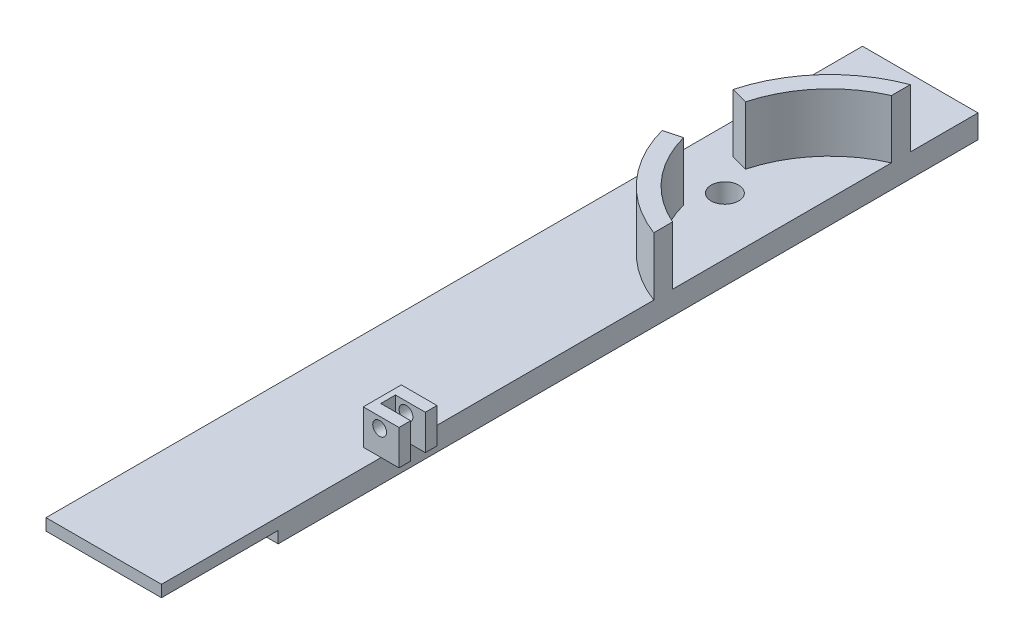
SolidWorks part; units mm, degrees
ref_plane "Front Plane" through (0, 0, 0) normal (0, 0, 1) x (1, 0, 0)
ref_plane "Top Plane" through (0, 0, 0) normal (0, 1, 0) x (1, 0, 0)
ref_plane "Right Plane" through (0, 0, 0) normal (1, 0, 0) x (0, 0, -1)
sketch "Sketch2" plane through (0, 0, 0) normal (0, 1, 0) x (1, 0, 0)
  line L1 (-10.6332, 33.9112) -> (14.5128, 33.9112)
  line L2 (-10.6332, 33.9112) -> (-10.6332, -143.8888)
  line L3 (-10.6332, -143.8888) -> (14.5128, -143.8888)
  line L4 (14.5128, 33.9112) -> (14.5128, -143.8888)
  dimension "D1" = 25.146
  dimension "D2" = 177.8
extrude "Boss-Extrude1" add sketch "Sketch2" along normal blind 5.08
sketch "Sketch4" plane through (0, 0, 0) normal (0, -1, 0) x (1, 0, 0)
  line L0 (14.5128, 143.8888) -> (14.5128, -33.9112) construction
  line L1 (-10.6332, 143.8888) -> (14.5128, 143.8888)
  line L2 (-10.6332, 143.8888) -> (-10.6332, 118.4888)
  line L3 (-10.6332, 118.4888) -> (14.5128, 118.4888)
  line L4 (14.5128, 143.8888) -> (14.5128, 118.4888)
  dimension "D1" = 25.4
extrude "Cut-Extrude2" cut sketch "Sketch4" against normal blind 2.54
sketch "Sketch5" plane through (0, 5.08, 0) normal (0, 1, 0) x (1, 0, 0)
  line L0 (14.5128, -143.8888) -> (14.5128, 33.9112) construction
  line L1 (14.5128, 33.9112) -> (-10.6332, 33.9112) construction
  line L2 (14.5128, 19.171) -> (14.5128, 15.0625)
  line L3 (14.5128, -32.5841) -> (14.5128, -36.6926)
  line L4 (24.9268, -8.7608) -> (-3.8674, -1.0454) construction
  line L5 (24.9268, -8.7608) -> (-3.8674, -16.4762) construction
  line L6 (24.9268, -8.7608) -> (-10.6332, -8.7608) construction
  line L7 (-10.6332, 33.9112) -> (-10.6332, -143.8888) construction
  line L8 (-3.8674, -1.0454) -> (-0.1872, -2.0315)
  line L9 (-3.8674, -16.4762) -> (-0.1872, -15.4901)
  arc A0 (14.5128, 15.0625) -> (-0.1872, -2.0315) centre (24.9268, -8.7608) ccw
  arc A1 (14.5128, 19.171) -> (-3.8674, -1.0454) centre (24.9268, -8.7608) ccw
  arc A2 (-0.1872, -15.4901) -> (14.5128, -32.5841) centre (24.9268, -8.7608) ccw
  arc A3 (-3.8674, -16.4762) -> (14.5128, -36.6926) centre (24.9268, -8.7608) ccw
  dimension "D1" = 10.414
  dimension "D2" = 42.672
  dimension "D3" = 3.81
  dimension "D4" = 52
  dimension "D5" = 15
  dimension "D6" = 15
extrude "Boss-Extrude2" add sketch "Sketch5" along normal blind 12.7
sketch "Sketch6" plane through (0, 0, 0) normal (0, -1, 0) x (1, 0, 0)
  line L0 (14.5128, 118.4888) -> (14.5128, -33.9112) construction
  line L1 (14.5128, -33.9112) -> (-10.6332, -33.9112) construction
  circle A0 centre (2.0668, 8.7608) radius 3
  dimension "D1" = 6
  dimension "D2" = 12.446
  dimension "D3" = 42.672
extrude "Cut-Extrude3" cut sketch "Sketch6" against normal through all
sketch "Sketch7" plane through (0, 5.08, 0) normal (0, 1, 0) x (1, 0, 0)
  line L0 (14.5128, -32.5841) -> (14.5128, 15.0625) construction
  line L1 (5.5918, -1.6036) -> (8.3544, -2.5309)
  line L2 (14.5128, 9.0329) -> (14.5128, 5.5572)
  line L3 (4.006, -16.4452) -> (6.7003, -15.8594)
  line L4 (14.5128, -28.4656) -> (14.5128, -25.3181)
  arc A0 (14.5128, -28.4656) -> (4.006, -16.4452) centre (24.9268, -8.7608) cw
  arc A1 (14.5128, 9.0329) -> (5.5918, -1.6036) centre (24.9268, -8.7608) ccw
  arc A2 (14.5128, 5.5572) -> (8.3544, -2.5309) centre (24.9268, -8.7608) ccw
  arc A3 (14.5128, -25.3181) -> (6.7003, -15.8594) centre (24.9268, -8.7608) cw
sketch "Sketch8" plane through (0, 5.08, 0) normal (0, 1, 0) x (1, 0, 0)
  line L0 (14.5128, -143.8888) -> (14.5128, -36.6926) construction
  line L1 (18.4097, -87.7914) -> (11.9097, -87.7914)
  line L2 (18.4097, -87.7914) -> (18.4097, -90.3314)
  line L3 (18.4097, -90.3314) -> (11.9097, -90.3314)
  line L4 (11.9097, -87.7914) -> (11.9097, -90.3314)
  line L6 (18.4097, -93.5314) -> (11.9097, -93.5314)
  line L7 (18.4097, -93.5314) -> (18.4097, -96.0714)
  line L8 (18.4097, -96.0714) -> (11.9097, -96.0714)
  line L9 (11.9097, -93.5314) -> (11.9097, -96.0714)
  line L10 (11.9097, -96.0714) -> (10.6397, -96.0714)
  line L11 (11.9097, -96.0714) -> (11.9097, -87.7914)
  line L12 (11.9097, -87.7914) -> (10.6397, -87.7914)
  line L13 (10.6397, -96.0714) -> (10.6397, -87.7914)
  line M24 (14.5128, -143.8888) -> (14.5128, -36.6926)
  dimension "D1" = 3.2
  dimension "D2" = 2.54
  dimension "D3" = 2.54
  dimension "D4" = 1.27
  dimension "D5" = 6.5
  dimension "D6" = 0
  dimension "D7" = 2.6032
extrude "Boss-Extrude3" add sketch "Sketch8" along normal blind 7.62 contours L13 L10 L9 L11 L4 L12 | L1 L4 L3 M24 | L6 L9 L8 M24
sketch "Sketch9" plane through (0, 0, 96.0714) normal (0, 0, 1) x (1, 0, 0)
  line L0 (10.6397, 5.4857) -> (14.1957, 5.4857) construction
  line L1 (10.6397, 12.7) -> (10.6397, 5.08) construction
  line L2 (14.1957, 5.08) -> (14.1957, 10.414) construction
  line L3 (14.5128, 5.08) -> (10.6397, 5.08) construction
  circle A0 centre (14.1957, 10.414) radius 1.5
  dimension "D1" = 3.556
  dimension "D2" = 5.334
extrude "Cut-Extrude4" cut sketch "Sketch9" against normal blind 10.668
